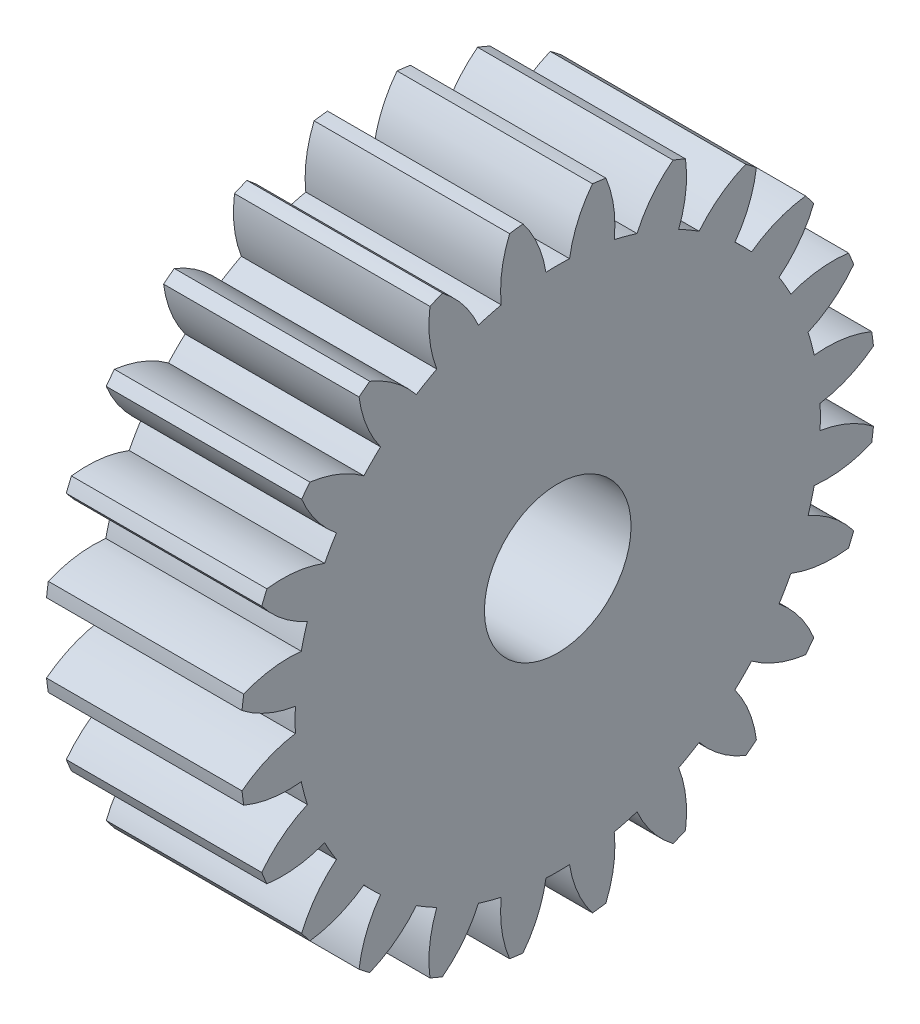
SolidWorks part; units mm, degrees
ref_plane "前视基准面" through (0, 0, 0) normal (0, 0, 1) x (1, 0, 0)
ref_plane "上视基准面" through (0, 0, 0) normal (0, 1, 0) x (1, 0, 0)
ref_plane "右视基准面" through (0, 0, 0) normal (1, 0, 0) x (0, 0, -1)
ref_plane "基准面4" through (4, 0, 0) normal (1, 0, 0) x (0, 0, -1)
sketch "草图1" plane through (4, 0, 0) normal (1, 0, 0) x (0, 0, -1)
  arc A0 (-5.3686, 0.2416) -> (-5.3686, -0.2416) centre (0, 0) ccw
  arc A1 (-5.3686, -0.2416) -> (-6.461, -0.7113) centre (-4.9963, -2.6126) ccw
  arc A2 (-6.461, -0.7113) -> (-6.4249, -0.9851) centre (0, 0) ccw
  arc A3 (-6.4249, -0.9851) -> (-5.2482, -1.1561) centre (-5.5023, 1.2304) ccw
  arc A4 (-5.2482, -1.1561) -> (-5.1231, -1.6229) centre (0, 0) ccw
  arc A5 (-5.1231, -1.6229) -> (-6.0567, -2.3593) centre (-4.1499, -3.8167) ccw
  arc A6 (-6.0567, -2.3593) -> (-5.951, -2.6144) centre (0, 0) ccw
  arc A7 (-5.951, -2.6144) -> (-4.7701, -2.475) centre (-5.6332, -0.2356) ccw
  arc A8 (-4.7701, -2.475) -> (-4.5285, -2.8936) centre (0, 0) ccw
  arc A9 (-4.5285, -2.8936) -> (-5.2397, -3.8465) centre (-3.0206, -4.7607) ccw
  arc A10 (-5.2397, -3.8465) -> (-5.0716, -4.0656) centre (0, 0) ccw
  arc A11 (-5.0716, -4.0656) -> (-3.967, -3.6253) centre (-5.3803, -1.6855) ccw
  arc A12 (-3.967, -3.6253) -> (-3.6253, -3.967) centre (0, 0) ccw
  arc A13 (-3.6253, -3.967) -> (-4.0656, -5.0716) centre (-1.6855, -5.3803) ccw
  arc A14 (-4.0656, -5.0716) -> (-3.8465, -5.2397) centre (0, 0) ccw
  arc A15 (-3.8465, -5.2397) -> (-2.8936, -4.5285) centre (-4.7607, -3.0206) ccw
  arc A16 (-2.8936, -4.5285) -> (-2.475, -4.7701) centre (0, 0) ccw
  arc A17 (-2.475, -4.7701) -> (-2.6144, -5.951) centre (-0.2356, -5.6332) ccw
  arc A18 (-2.6144, -5.951) -> (-2.3593, -6.0567) centre (0, 0) ccw
  arc A19 (-2.3593, -6.0567) -> (-1.6229, -5.1231) centre (-3.8167, -4.1499) ccw
  arc A20 (-1.6229, -5.1231) -> (-1.1561, -5.2482) centre (0, 0) ccw
  arc A21 (-1.1561, -5.2482) -> (-0.9851, -6.4249) centre (1.2304, -5.5023) ccw
  arc A22 (-0.9851, -6.4249) -> (-0.7113, -6.461) centre (0, 0) ccw
  arc A23 (-0.7113, -6.461) -> (-0.2416, -5.3686) centre (-2.6126, -4.9963) ccw
  arc A24 (-0.2416, -5.3686) -> (0.2416, -5.3686) centre (0, 0) ccw
  arc A25 (0.2416, -5.3686) -> (0.7113, -6.461) centre (2.6126, -4.9963) ccw
  arc A26 (0.7113, -6.461) -> (0.9851, -6.4249) centre (0, 0) ccw
  arc A27 (0.9851, -6.4249) -> (1.1561, -5.2482) centre (-1.2304, -5.5023) ccw
  arc A28 (1.1561, -5.2482) -> (1.6229, -5.1231) centre (0, 0) ccw
  arc A29 (1.6229, -5.1231) -> (2.3593, -6.0567) centre (3.8167, -4.1499) ccw
  arc A30 (2.3593, -6.0567) -> (2.6144, -5.951) centre (0, 0) ccw
  arc A31 (2.6144, -5.951) -> (2.475, -4.7701) centre (0.2356, -5.6332) ccw
  arc A32 (2.475, -4.7701) -> (2.8936, -4.5285) centre (0, 0) ccw
  arc A33 (2.8936, -4.5285) -> (3.8465, -5.2397) centre (4.7607, -3.0206) ccw
  arc A34 (3.8465, -5.2397) -> (4.0656, -5.0716) centre (0, 0) ccw
  arc A35 (4.0656, -5.0716) -> (3.6253, -3.967) centre (1.6855, -5.3803) ccw
  arc A36 (3.6253, -3.967) -> (3.967, -3.6253) centre (0, 0) ccw
  arc A37 (3.967, -3.6253) -> (5.0716, -4.0656) centre (5.3803, -1.6855) ccw
  arc A38 (5.0716, -4.0656) -> (5.2397, -3.8465) centre (0, 0) ccw
  arc A39 (5.2397, -3.8465) -> (4.5285, -2.8936) centre (3.0206, -4.7607) ccw
  arc A40 (4.5285, -2.8936) -> (4.7701, -2.475) centre (0, 0) ccw
  arc A41 (4.7701, -2.475) -> (5.951, -2.6144) centre (5.6332, -0.2356) ccw
  arc A42 (5.951, -2.6144) -> (6.0567, -2.3593) centre (0, 0) ccw
  arc A43 (6.0567, -2.3593) -> (5.1231, -1.6229) centre (4.1499, -3.8167) ccw
  arc A44 (5.1231, -1.6229) -> (5.2482, -1.1561) centre (0, 0) ccw
  arc A45 (5.2482, -1.1561) -> (6.4249, -0.9851) centre (5.5023, 1.2304) ccw
  arc A46 (6.4249, -0.9851) -> (6.461, -0.7113) centre (0, 0) ccw
  arc A47 (6.461, -0.7113) -> (5.3686, -0.2416) centre (4.9963, -2.6126) ccw
  arc A48 (5.3686, -0.2416) -> (5.3686, 0.2416) centre (0, 0) ccw
  arc A49 (5.3686, 0.2416) -> (6.461, 0.7113) centre (4.9963, 2.6126) ccw
  arc A50 (6.461, 0.7113) -> (6.4249, 0.9851) centre (0, 0) ccw
  arc A51 (6.4249, 0.9851) -> (5.2482, 1.1561) centre (5.5023, -1.2304) ccw
  arc A52 (5.2482, 1.1561) -> (5.1231, 1.6229) centre (0, 0) ccw
  arc A53 (5.1231, 1.6229) -> (6.0567, 2.3593) centre (4.1499, 3.8167) ccw
  arc A54 (6.0567, 2.3593) -> (5.951, 2.6144) centre (0, 0) ccw
  arc A55 (5.951, 2.6144) -> (4.7701, 2.475) centre (5.6332, 0.2356) ccw
  arc A56 (4.7701, 2.475) -> (4.5285, 2.8936) centre (0, 0) ccw
  arc A57 (4.5285, 2.8936) -> (5.2397, 3.8465) centre (3.0206, 4.7607) ccw
  arc A58 (5.2397, 3.8465) -> (5.0716, 4.0656) centre (0, 0) ccw
  arc A59 (5.0716, 4.0656) -> (3.967, 3.6253) centre (5.3803, 1.6855) ccw
  arc A60 (3.967, 3.6253) -> (3.6253, 3.967) centre (0, 0) ccw
  arc A61 (3.6253, 3.967) -> (4.0656, 5.0716) centre (1.6855, 5.3803) ccw
  arc A62 (4.0656, 5.0716) -> (3.8465, 5.2397) centre (0, 0) ccw
  arc A63 (3.8465, 5.2397) -> (2.8936, 4.5285) centre (4.7607, 3.0206) ccw
  arc A64 (2.8936, 4.5285) -> (2.475, 4.7701) centre (0, 0) ccw
  arc A65 (2.475, 4.7701) -> (2.6144, 5.951) centre (0.2356, 5.6332) ccw
  arc A66 (2.6144, 5.951) -> (2.3593, 6.0567) centre (0, 0) ccw
  arc A67 (2.3593, 6.0567) -> (1.6229, 5.1231) centre (3.8167, 4.1499) ccw
  arc A68 (1.6229, 5.1231) -> (1.1561, 5.2482) centre (0, 0) ccw
  arc A69 (1.1561, 5.2482) -> (0.9851, 6.4249) centre (-1.2304, 5.5023) ccw
  arc A70 (0.9851, 6.4249) -> (0.7113, 6.461) centre (0, 0) ccw
  arc A71 (0.7113, 6.461) -> (0.2416, 5.3686) centre (2.6126, 4.9963) ccw
  arc A72 (0.2416, 5.3686) -> (-0.2416, 5.3686) centre (0, 0) ccw
  arc A73 (-0.2416, 5.3686) -> (-0.7113, 6.461) centre (-2.6126, 4.9963) ccw
  arc A74 (-0.7113, 6.461) -> (-0.9851, 6.4249) centre (0, 0) ccw
  arc A75 (-0.9851, 6.4249) -> (-1.1561, 5.2482) centre (1.2304, 5.5023) ccw
  arc A76 (-1.1561, 5.2482) -> (-1.6229, 5.1231) centre (0, 0) ccw
  arc A77 (-1.6229, 5.1231) -> (-2.3593, 6.0567) centre (-3.8167, 4.1499) ccw
  arc A78 (-2.3593, 6.0567) -> (-2.6144, 5.951) centre (0, 0) ccw
  arc A79 (-2.6144, 5.951) -> (-2.475, 4.7701) centre (-0.2356, 5.6332) ccw
  arc A80 (-2.475, 4.7701) -> (-2.8936, 4.5285) centre (0, 0) ccw
  arc A81 (-2.8936, 4.5285) -> (-3.8465, 5.2397) centre (-4.7607, 3.0206) ccw
  arc A82 (-3.8465, 5.2397) -> (-4.0656, 5.0716) centre (0, 0) ccw
  arc A83 (-4.0656, 5.0716) -> (-3.6253, 3.967) centre (-1.6855, 5.3803) ccw
  arc A84 (-3.6253, 3.967) -> (-3.967, 3.6253) centre (0, 0) ccw
  arc A85 (-3.967, 3.6253) -> (-5.0716, 4.0656) centre (-5.3803, 1.6855) ccw
  arc A86 (-5.0716, 4.0656) -> (-5.2397, 3.8465) centre (0, 0) ccw
  arc A87 (-5.2397, 3.8465) -> (-4.5285, 2.8936) centre (-3.0206, 4.7607) ccw
  arc A88 (-4.5285, 2.8936) -> (-4.7701, 2.475) centre (0, 0) ccw
  arc A89 (-4.7701, 2.475) -> (-5.951, 2.6144) centre (-5.6332, 0.2356) ccw
  arc A90 (-5.951, 2.6144) -> (-6.0567, 2.3593) centre (0, 0) ccw
  arc A91 (-6.0567, 2.3593) -> (-5.1231, 1.6229) centre (-4.1499, 3.8167) ccw
  arc A92 (-5.1231, 1.6229) -> (-5.2482, 1.1561) centre (0, 0) ccw
  arc A93 (-5.2482, 1.1561) -> (-6.4249, 0.9851) centre (-5.5023, -1.2304) ccw
  arc A94 (-6.4249, 0.9851) -> (-6.461, 0.7113) centre (0, 0) ccw
  arc A95 (-6.461, 0.7113) -> (-5.3686, 0.2416) centre (-4.9963, 2.6126) ccw
  circle A96 centre (0, 0) radius 1.5
extrude "凸台-拉伸1" add sketch "草图1" against normal blind 4
chamfer "倒角1" distance 0.1 angle 45 1 edges at (0, 0, 1.5)
